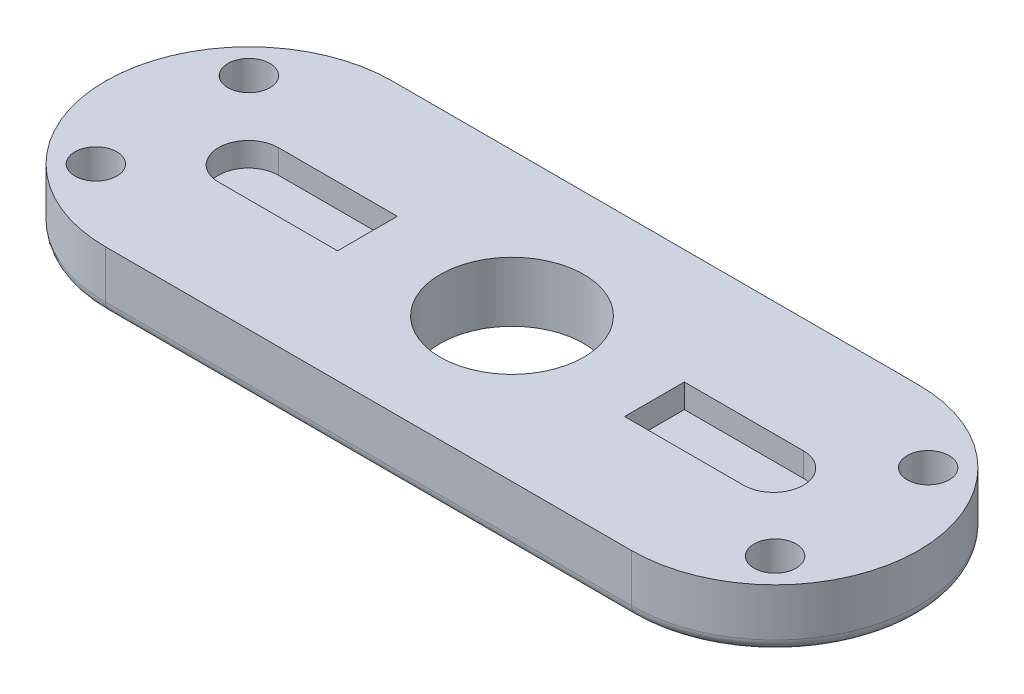
SolidWorks part; units mm, degrees
ref_plane "Front Plane" through (0, 0, 0) normal (0, 0, 1) x (1, 0, 0)
ref_plane "Top Plane" through (0, 0, 0) normal (0, 1, 0) x (1, 0, 0)
ref_plane "Right Plane" through (0, 0, 0) normal (1, 0, 0) x (0, 0, -1)
sketch "Sketch1" plane through (0, 0, 0) normal (0, 1, 0) x (1, 0, 0)
  line L0 (27.94, 15.24) -> (-27.94, 15.24)
  line L5 (-27.94, -15.24) -> (27.94, -15.24)
  arc A0 (27.94, 15.24) -> (27.94, -15.24) centre (27.94, 0) cw
  arc A1 (-27.94, 15.24) -> (-27.94, -15.24) centre (-27.94, 0) ccw
  point P0 (0, 0)
extrude "Boss-Extrude1" add sketch "Sketch1" along normal blind 6.35
sketch "Sketch2" plane through (0, 6.35, 0) normal (0, 1, 0) x (1, 0, 0)
  line L0 (0, 0) -> (-15.24, 0) construction
  line L1 (0, 0) -> (0, -15.24) construction
  line L2 (-27.94, -15.24) -> (27.94, -15.24) construction
  line L3 (0, -15.24) -> (0, 15.24) construction
  line L4 (27.94, 15.24) -> (-27.94, 15.24) construction
  line L5 (-27.94, 15.24) -> (-27.94, -15.24) construction
  line L6 (-15.24, 3.0634) -> (-27.8827, 3.0634)
  line L7 (-15.24, 3.0634) -> (-15.24, -3.2866)
  line L8 (-15.24, -3.2866) -> (-27.8827, -3.2866)
  line L10 (-43.18, 0) -> (43.18, 0) construction
  line L11 (15.24, 3.0634) -> (15.24, -3.2866)
  line L12 (15.24, -3.2866) -> (27.8827, -3.2866)
  line L13 (15.24, 3.0634) -> (27.8827, 3.0634)
  arc A0 (-27.94, 15.24) -> (-27.94, -15.24) centre (-27.94, 0) ccw construction
  arc A1 (27.94, -15.24) -> (27.94, 15.24) centre (27.94, 0) ccw construction
  arc A2 (-27.8827, 3.0634) -> (-27.8827, -3.2866) centre (-27.8827, -0.1116) ccw
  arc A5 (27.8827, 3.0634) -> (27.8827, -3.2866) centre (27.8827, -0.1116) cw
  dimension "D1" = 15.24
  dimension "D2" = 6.35
extrude "Cut-Extrude1" cut sketch "Sketch2" against normal blind 2.54
sketch "Sketch3" plane through (0, 6.35, 0) normal (0, 1, 0) x (1, 0, 0)
  circle A0 centre (0, 0) radius 7.62
  dimension "D1" = 15.24
extrude "Cut-Extrude2" cut sketch "Sketch3" against normal through all
sketch "Sketch4" plane through (0, 6.35, 0) normal (0, 1, 0) x (1, 0, 0)
  line L0 (0, 0) -> (-43.18, 0) construction
  line L1 (-43.18, 0) -> (43.18, 0) construction
  line L2 (27.94, 15.24) -> (27.94, -15.24) construction
  line L3 (-27.94, 15.24) -> (-27.94, -15.24) construction
  line L4 (0, -15.24) -> (0, 15.24) construction
  line L5 (-27.94, -15.24) -> (27.94, -15.24) construction
  line L6 (27.94, 15.24) -> (-27.94, 15.24) construction
  arc A0 (-27.94, 15.24) -> (-27.94, -15.24) centre (-27.94, 0) ccw construction
  arc A1 (27.94, -15.24) -> (27.94, 15.24) centre (27.94, 0) ccw construction
  circle A2 centre (-36.068, 8.128) radius 2.2339
  circle A3 centre (-36.068, -8.128) radius 2.2339
  circle A4 centre (36.068, 8.128) radius 2.2339
  circle A5 centre (36.068, -8.128) radius 2.2339
  dimension "D1" = 4.4679
  dimension "D2" = 4.4679
  dimension "D3" = 8.128
  dimension "D5" = 8.128
  dimension "D6" = 8.128
  dimension "D4" = 8.128
fillet "Fillet1" radius 1.27 4 edges at (-43.18, 0, 0) (0, 0, -15.24) (43.18, 0, 0) (0, 0, 15.24)
sketch "Sketch6" plane through (0, 6.35, 0) normal (0, 1, 0) x (1, 0, 0)
  line L0 (0, 0) -> (0, 15.24) construction
  line L1 (0, 15.24) -> (0, -15.24) construction
  line L2 (-27.94, -15.24) -> (27.94, -15.24) construction
  line L3 (-43.18, 0) -> (43.18, 0) construction
  point P0 (-36.068, 8.128)
  point P1 (-36.068, -8.128)
  point P3 (36.068, -8.128)
  point P5 (-36.068, -8.128)
  point P7 (-36.068, 8.128)
  point P8 (36.068, 8.128)
extrude "Cut-Extrude3" cut sketch "Sketch4" against normal through all
